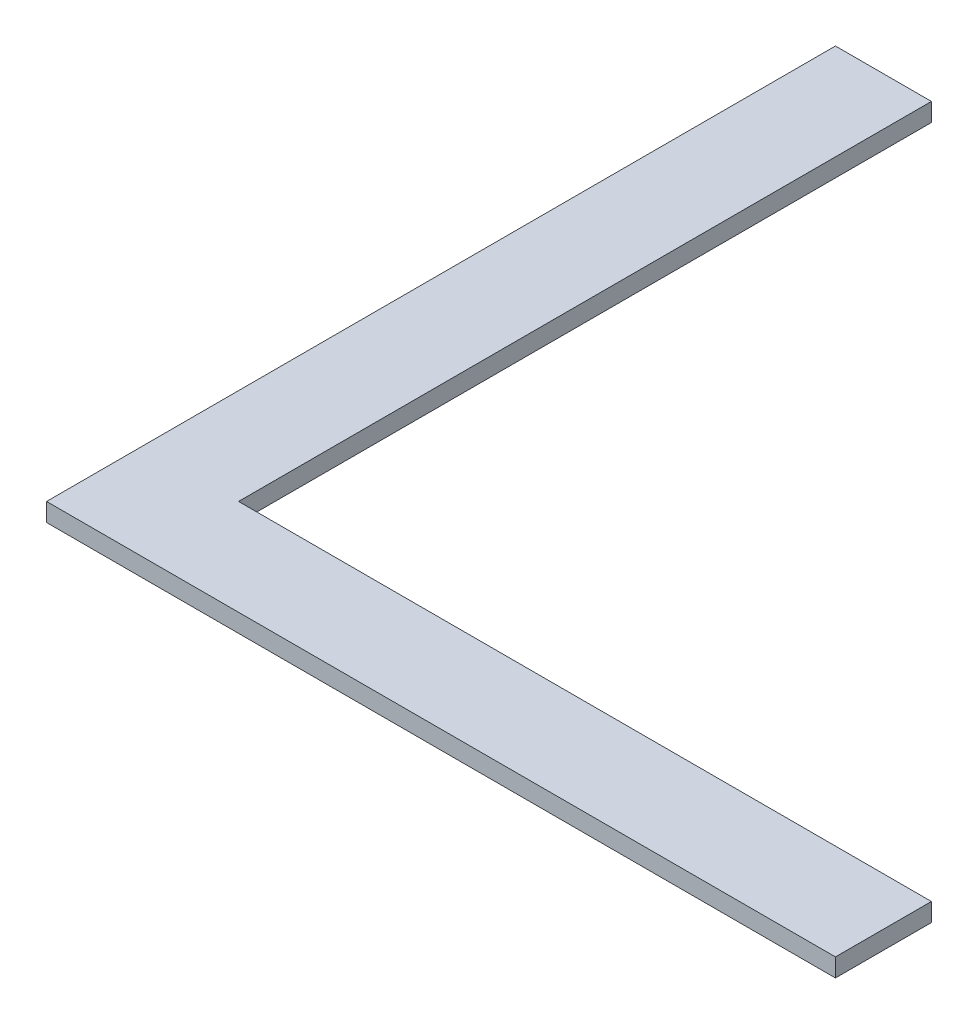
SolidWorks part; units mm, degrees
ref_plane "Front Plane" through (0, 0, 0) normal (0, 0, 1) x (1, 0, 0)
ref_plane "Top Plane" through (0, 0, 0) normal (0, 1, 0) x (1, 0, 0)
ref_plane "Right Plane" through (0, 0, 0) normal (1, 0, 0) x (0, 0, -1)
sketch "Sketch1" plane through (0, 0, 0) normal (0, 1, 0) x (1, 0, 0)
  line L0 (-5.25, 37.9) -> (-5.25, -5.25)
  line L1 (-5.25, -5.25) -> (37.9, -5.25)
  line L2 (37.9, -5.25) -> (37.9, 0)
  line L3 (37.9, 0) -> (0, 0)
  line L4 (0, 0) -> (0, 37.9)
  line L5 (0, 37.9) -> (-5.25, 37.9)
  point P3 (0, 0)
  dimension "D1" = 43.15
  dimension "D2" = 5.25
extrude "Boss-Extrude1" add sketch "Sketch1" along normal blind 1
